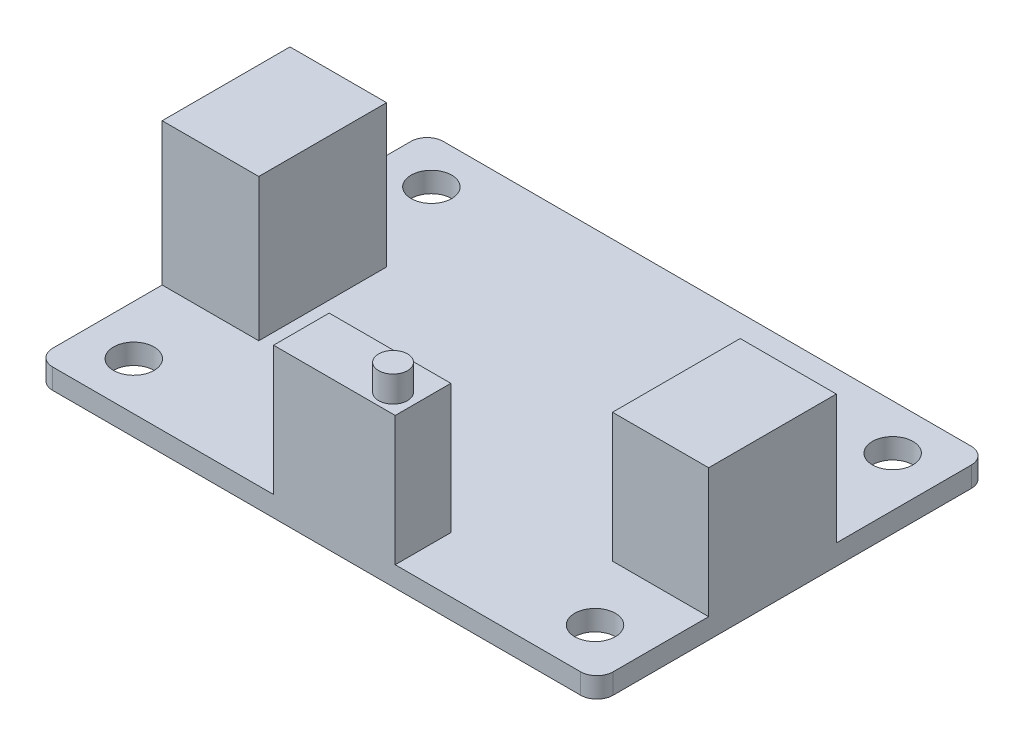
SolidWorks part; units mm, degrees
ref_plane "Front Plane" through (0, 0, 0) normal (0, 0, 1) x (1, 0, 0)
ref_plane "Top Plane" through (0, 0, 0) normal (0, 1, 0) x (1, 0, 0)
ref_plane "Right Plane" through (0, 0, 0) normal (1, 0, 0) x (0, 0, -1)
sketch "Sketch1" plane through (0, 0, 0) normal (0, 1, 0) x (1, 0, 0)
  line L1 (-20.6124, -15.3467) -> (20.6118, -15.3467)
  line L2 (-21.8824, -14.0767) -> (-21.8824, 13.8887)
  line L3 (-20.6124, 15.1587) -> (20.6118, 15.1587)
  line L4 (21.8818, -14.0767) -> (21.8818, 13.8887)
  line L5 (-21.8821, -15.2527) -> (21.8817, 15.2524) construction
  line L6 (-21.8824, 15.1587) -> (22.018, -15.2526) construction
  circle A0 centre (-18.0086, 11.6205) radius 1.5875
  circle A1 centre (-18.0086, -11.6205) radius 1.5875
  circle A2 centre (18.0086, 11.6205) radius 1.5875
  circle A3 centre (18.0086, -11.6205) radius 1.5875
  arc A4 (-21.8824, 13.8887) -> (-20.6124, 15.1587) centre (-20.6124, 13.8887) cw
  arc A5 (-21.8824, -14.0767) -> (-20.6124, -15.3467) centre (-20.6124, -14.0767) ccw
  arc A6 (21.8818, -14.0767) -> (20.6118, -15.3467) centre (20.6118, -14.0767) cw
  arc A7 (21.8818, 13.8887) -> (20.6118, 15.1587) centre (20.6118, 13.8887) ccw
  point P0 (0, 0)
  point P9 (0, 0)
  dimension "D3" = 1.27
  dimension "D1" = 43.7642
  dimension "D2" = 30.5054
extrude "Boss-Extrude4" add sketch "Sketch1" along normal blind 1.5875 contours L4 A7 L3 A4 L2 A5 L1 A6 A2 A0 A1 A3
sketch "Sketch2" plane through (0, 1.5875, 0) normal (0, 1, 0) x (1, 0, 0)
  line L2 (21.8818, -14.0767) -> (21.8818, 13.8887) construction
  line L6 (14.3761, -6.6218) -> (21.8818, -6.6218)
  line L7 (14.3761, -6.6218) -> (14.3761, 3.3477)
  line L8 (14.3761, 3.3477) -> (21.8818, 3.3477)
  line L9 (21.8818, -6.6218) -> (21.8818, 3.3477)
extrude "Boss-Extrude5" add sketch "Sketch2" along normal blind 10.0711 contours L7 L6 L9 L8
sketch "Sketch3" plane through (0, 1.5875, 0) normal (0, 1, 0) x (1, 0, 0)
  line L2 (-20.6124, -15.3467) -> (20.6118, -15.3467) construction
  line L5 (-3.3658, -11.0033) -> (6.1338, -11.0033)
  line L6 (-3.3658, -11.0033) -> (-3.3658, -15.3467)
  line L7 (-3.3658, -15.3467) -> (6.1338, -15.3467)
  line L8 (6.1338, -11.0033) -> (6.1338, -15.3467)
extrude "Boss-Extrude6" add sketch "Sketch3" along normal blind 10.0965 contours L6 L5 L8 L7
sketch "Sketch5" plane through (0, 11.684, 0) normal (0, 1, 0) x (1, 0, 0)
  circle A0 centre (4.4857, -13.8659) radius 1.1303
extrude "Boss-Extrude7" add sketch "Sketch5" along normal blind 2.032
sketch "Sketch6" plane through (0, 1.5875, 0) normal (0, 1, 0) x (1, 0, 0)
  line L2 (-21.8824, -14.0767) -> (-21.8824, 13.8887) construction
  line L4 (-21.8824, 4.4526) -> (-14.3386, 4.4526)
  line L6 (-14.3386, 4.4526) -> (-21.8824, 4.4526)
  line L7 (-14.3386, 4.4526) -> (-14.3386, -5.5296)
  line L8 (-14.3386, -5.5296) -> (-21.8824, -5.5296)
  line L9 (-21.8824, 4.4526) -> (-21.8824, -5.5296)
  point P7 (0, 0)
extrude "Boss-Extrude8" add sketch "Sketch6" along normal blind 11.1125 contours L7 L6 L9 L8
